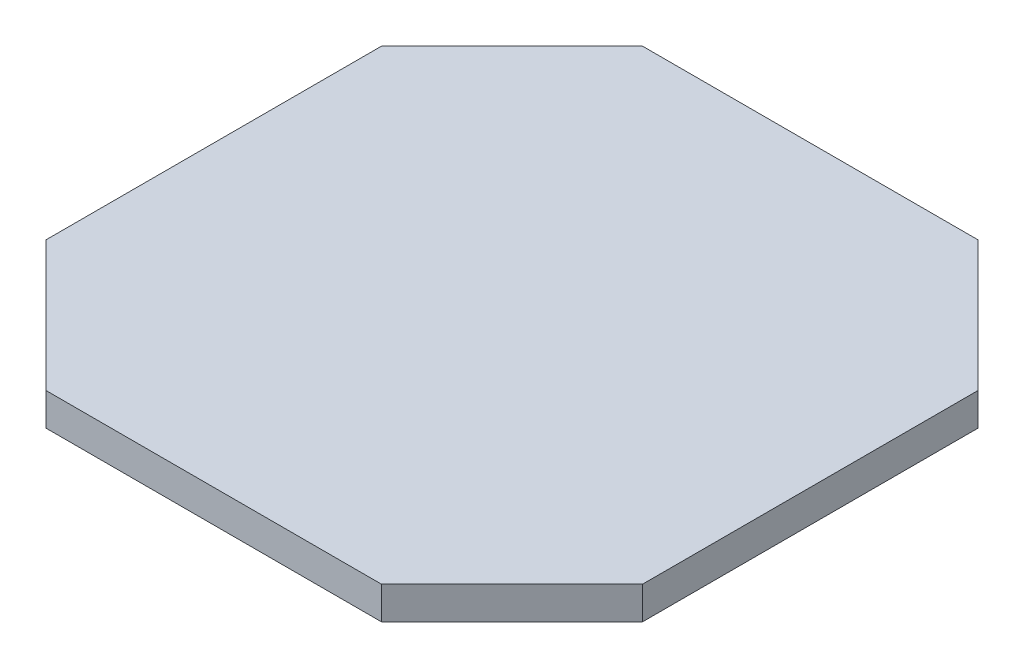
SolidWorks part; units mm, degrees
ref_plane "Front Plane" through (0, 0, 0) normal (0, 0, 1) x (1, 0, 0)
ref_plane "Top Plane" through (0, 0, 0) normal (0, 1, 0) x (1, 0, 0)
ref_plane "Right Plane" through (0, 0, 0) normal (1, 0, 0) x (0, 0, -1)
sketch "Sketch1" plane through (0, 0, 0) normal (0, 1, 0) x (1, 0, 0)
  line L1 (-16, 16) -> (16, 16)
  line L2 (-16, 16) -> (-16, -16)
  line L3 (-16, -16) -> (16, -16)
  line L4 (16, 16) -> (16, -16)
  line L5 (-16, 16) -> (16, -16) construction
  line L6 (-16, -16) -> (16, 16) construction
  point P0 (0, 0)
  dimension "D2" = 32
  dimension "D3" = 32
extrude "Boss-Extrude1" add sketch "Sketch1" against normal blind 1.75
chamfer "Chamfer1" distance 7 angle 45 4 edges at (16, -0.875, -16) (16, -0.875, 16) (-16, -0.875, 16) (-16, -0.875, -16)
